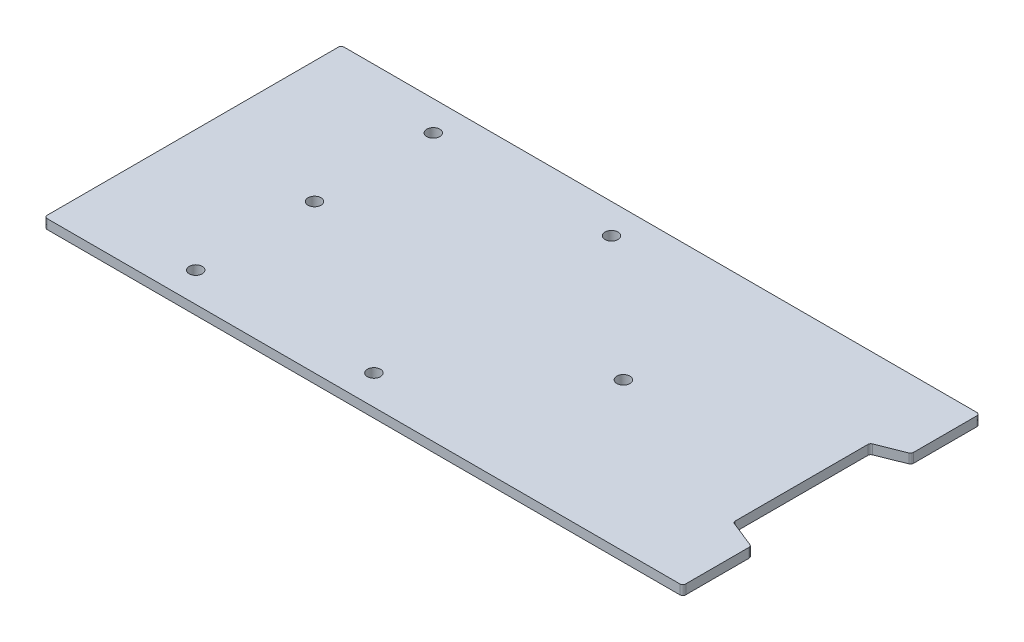
SolidWorks part; units mm, degrees
ref_plane "Front Plane" through (0, 0, 0) normal (0, 0, 1) x (1, 0, 0)
ref_plane "Top Plane" through (0, 0, 0) normal (0, 1, 0) x (1, 0, 0)
ref_plane "Right Plane" through (0, 0, 0) normal (1, 0, 0) x (0, 0, -1)
sketch "Sketch1" plane through (0, 0, 0) normal (0, 1, 0) x (1, 0, 0)
  line L0 (102.5, 50) -> (106.9926, 50)
  line L1 (0.5074, 0) -> (102.5, 0)
  line L2 (0, 0.5074) -> (0, 49.4926)
  line L3 (0.5074, 50) -> (102.5, 50)
  line L4 (102.5, 13.8435) -> (102.5, 36.1565)
  line L5 (107.5, 49.4926) -> (107.5, 38.8435)
  line L6 (107.181, 38.3724) -> (102.819, 36.6276)
  line L7 (0, 25) -> (160.2024, 25) construction
  line L8 (107.181, 11.6276) -> (102.819, 13.3724)
  line L9 (102.5, 0) -> (106.9926, 0)
  line L10 (107.5, 0.5074) -> (107.5, 11.1565)
  arc A0 (0.5074, 0) -> (0, 0.5074) centre (0.5074, 0.5074) cw
  arc A1 (0, 49.4926) -> (0.5074, 50) centre (0.5074, 49.4926) cw
  arc A2 (106.9926, 0) -> (107.5, 0.5074) centre (106.9926, 0.5074) ccw
  arc A3 (107.181, 11.6276) -> (107.5, 11.1565) centre (106.9926, 11.1565) cw
  arc A4 (102.819, 13.3724) -> (102.5, 13.8435) centre (103.0074, 13.8435) cw
  arc A5 (102.819, 36.6276) -> (102.5, 36.1565) centre (103.0074, 36.1565) ccw
  arc A6 (107.5, 38.8435) -> (107.181, 38.3724) centre (106.9926, 38.8435) cw
  arc A7 (106.9926, 50) -> (107.5, 49.4926) centre (106.9926, 49.4926) cw
  point P13 (0, 0)
  point P16 (0, 0)
  point P21 (107.5, 0)
  point P24 (107.5, 11.5)
  point P27 (102.5, 13.5)
  point P30 (102.5, 36.5)
  point P33 (107.5, 38.5)
  point P36 (107.5, 50)
  dimension "D6" = 0.5074
  dimension "D1" = 50
  dimension "D2" = 102.5
  dimension "D3" = 11.5
  dimension "D4" = 2
  dimension "D5" = 5
extrude "Boss-Extrude1" add sketch "Sketch1" along normal blind 1.6 contours L1 L9 A2 L10 A3 L8 A4 L4 A5 L6 A6 L5 A7 L0 L3 A1 L2 A0
sketch "Sketch2" plane through (0, 1.6, 0) normal (0, 1, 0) x (1, 0, 0)
  line L0 (0, 0.5074) -> (0, 49.4926) construction
  line L1 (0.5074, 0) -> (106.9926, 0) construction
  circle A0 centre (20.5, 5) radius 1.1
  circle A1 centre (20.5, 25) radius 1.1
  circle A2 centre (20.5, 45) radius 1.1
  circle A3 centre (50.5, 45) radius 1.1
  circle A4 centre (50.5, 5) radius 1.1
  circle A5 centre (72.5, 25) radius 1.1
  dimension "D1" = 2.2
  dimension "D2" = 20.5
  dimension "D3" = 5
  dimension "D4" = 25
  dimension "D5" = 45
  dimension "D6" = 50.5
  dimension "D7" = 72.5
extrude "Cut-Extrude1" cut sketch "Sketch2" against normal through all
